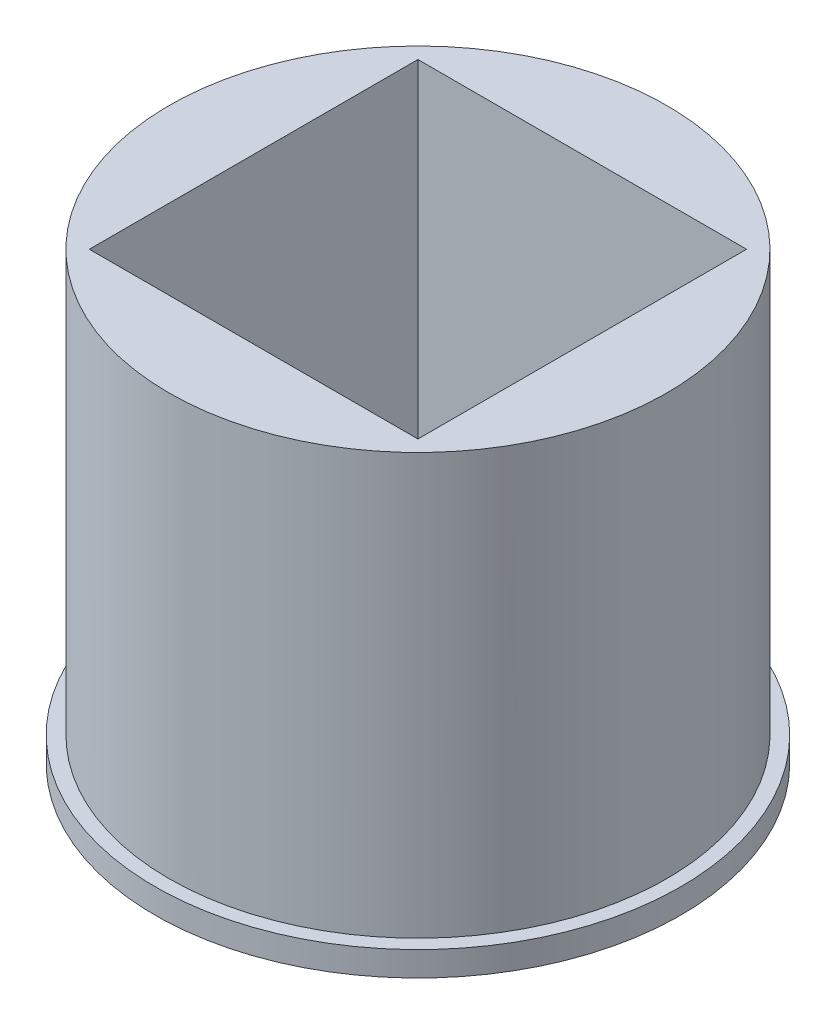
SolidWorks part; units mm, degrees
ref_plane "Front Plane" through (0, 0, 0) normal (0, 0, 1) x (1, 0, 0)
ref_plane "Top Plane" through (0, 0, 0) normal (0, 1, 0) x (1, 0, 0)
ref_plane "Right Plane" through (0, 0, 0) normal (1, 0, 0) x (0, 0, -1)
sketch "Sketch1" plane through (0, 0, 0) normal (0, 1, 0) x (1, 0, 0)
  line L1 (10, -10) -> (-10, -10)
  line L2 (10, -10) -> (10, 10)
  line L3 (10, 10) -> (-10, 10)
  line L4 (-10, -10) -> (-10, 10)
  line L5 (10, -10) -> (-10, 10) construction
  line L6 (10, 10) -> (-10, -10) construction
  circle A0 centre (0, 0) radius 15
  dimension "D1" = 20
  dimension "D3" = 30
  dimension "D2" = 20
extrude "Boss-Extrude1" add sketch "Sketch1" along normal blind 27.1
sketch "Sketch2" plane through (0, 0, 0) normal (0, -1, 0) x (1, 0, 0)
  circle A0 centre (0, 0) radius 16
extrude "Boss-Extrude2" add sketch "Sketch2" along normal blind 1.5
sketch "Sketch3" plane through (0, 27.1, 0) normal (0, 1, 0) x (1, 0, 0)
  line L0 (10, 10) -> (-10, 10) construction
  line L1 (-10, 10) -> (-10, -10) construction
  line L2 (10, 10) -> (-10, 10)
  line L3 (-10, 10) -> (-10, -10)
  line L4 (-10, -10) -> (10, -10)
  line L5 (-10, 10) -> (-10, -10)
  line L6 (10, 10) -> (-10, 10)
  line L7 (10, -10) -> (10, 10)
  line L8 (-10, -10) -> (10, -10)
  line L9 (-10, 10) -> (-10, -10)
  line L10 (10, 10) -> (-10, 10)
  line L11 (10, -10) -> (10, 10)
  circle A0 centre (0, 0) radius 15.15
  circle M6 centre (0, 0) radius 15
  line M7 (10, -10) -> (-10, -10)
  line M8 (-10, -10) -> (-10, 10)
  line M9 (-10, 10) -> (10, 10)
  line M10 (10, 10) -> (10, -10)
  dimension "D1" = 0
extrude "Boss-Extrude4" add sketch "Sketch3" against normal up to surface (27.1 mm away) contours M6 M10 M7 M8 M9 | A0 M6 up to face at (0, 0, 15)
sketch "Sketch4" plane through (0, 27.1, 0) normal (0, 1, 0) x (1, 0, 0)
  circle A1 centre (0, 0) radius 15.15
  circle A2 centre (0, 0) radius 15.15
  dimension "D1" = 0
extrude "Cut-Extrude1" cut sketch "Sketch4" against normal blind 1.5
